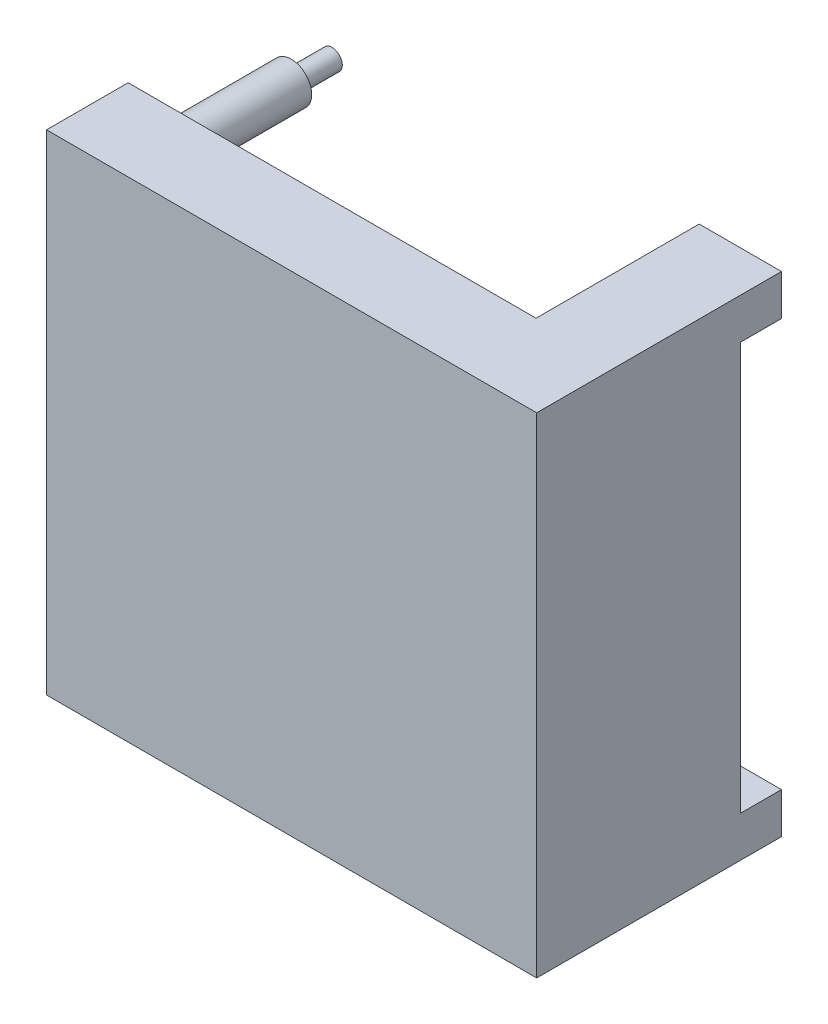
SolidWorks part; units mm, degrees
ref_plane "前视基准面" through (0, 0, 0) normal (0, 0, 1) x (1, 0, 0)
ref_plane "上视基准面" through (0, 0, 0) normal (0, 1, 0) x (1, 0, 0)
ref_plane "右视基准面" through (0, 0, 0) normal (1, 0, 0) x (0, 0, -1)
sketch "草图1" plane through (0, 0, 0) normal (0, 1, 0) x (1, 0, 0)
  line L0 (0, 0) -> (120.1627, 0)
  line L1 (120.1627, 0) -> (120.1627, 60)
  line L2 (120.1627, 60) -> (100, 60)
  line L3 (100, 60) -> (100, 20)
  line L4 (100, 20) -> (0, 20)
  line L5 (0, 20) -> (0, 0)
extrude "凸台-拉伸1" add sketch "草图1" along normal blind 60
sketch "草图3" plane through (120.1627, 0, 0) normal (1, 0, 0) x (0, 0, -1)
  line L0 (60, 50) -> (60, 10)
  line L1 (60, 60) -> (60, 0) construction
  line L2 (60, 10) -> (50, 10)
  line L3 (50, 10) -> (50, 50)
  line L5 (60, 50) -> (50, 50)
extrude "切除-拉伸2" cut sketch "草图3" against normal through all
sketch "草图4" plane through (0, 0, -20) normal (0, 0, -1) x (-1, 0, 0)
  line L2 (-100, 0) -> (0, 0) construction
  circle A0 centre (-10, 10) radius 5
  circle A1 centre (-10, 50) radius 5
  dimension "D1" = 10
sketch "草图6" plane through (0, 0, 0) normal (0, -1, 0) x (1, 0, 0)
  line L0 (42.3732, -30.9565) -> (41.9663, -30.9565)
sketch "草图7" plane through (0, 60, 0) normal (0, 1, 0) x (1, 0, 0)
  line L0 (0, 20) -> (0, 0)
  line L1 (0, 0) -> (120.1627, 0)
  line L2 (120.1627, 0) -> (120.1627, 60)
  line L3 (120.1627, 60) -> (100, 60)
  line L4 (100, 60) -> (100, 20)
  line L5 (100, 20) -> (0, 20)
extrude "凸台-拉伸4" add sketch "草图7" along normal blind 30
sketch "草图8" plane through (0, 0, 0) normal (0, -1, 0) x (1, 0, 0)
  line L0 (0, -20) -> (0, 0)
  line L1 (0, 0) -> (120.1627, 0)
  line L2 (120.1627, 0) -> (120.1627, -60)
  line L3 (120.1627, -60) -> (100, -60)
  line L4 (100, -60) -> (100, -20)
  line L5 (100, -20) -> (0, -20)
extrude "凸台-拉伸5" add sketch "草图8" along normal blind 30
sketch "草图9" plane through (0, 0, -20) normal (0, 0, -1) x (-1, 0, 0)
  line L0 (0, 30) -> (-20, 30)
  line L1 (0, 90) -> (0, -30) construction
  line L2 (-10, 30) -> (-10, -20)
  circle A0 centre (-10, -20) radius 5
  circle A1 centre (-10, 80) radius 5
extrude "凸台-拉伸6" add sketch "草图9" along normal blind 30 contours A1 | A0
sketch "草图10" plane through (0, 0, -50) normal (0, 0, -1) x (-1, 0, 0)
  circle A0 centre (-10, -20) radius 2.5
  circle A1 centre (-10, 80) radius 2.5
extrude "凸台-拉伸7" add sketch "草图10" along normal blind 10
sketch "草图11" plane through (0, 0, -60) normal (0, 0, -1) x (-1, 0, 0)
  line L0 (-120.1627, 10) -> (-100, 10)
  line L1 (-100, 10) -> (-100, -20)
  line L2 (-100, 90) -> (-100, -30) construction
  line L3 (-100, -20) -> (-120.1627, -20)
  line L4 (-120.1627, 10) -> (-120.1627, -30) construction
  line L5 (-120.1627, -20) -> (-120.1627, 10)
  line L6 (-120.1627, 50) -> (-100, 50)
  line L7 (-100, 50) -> (-100, 80)
  line L8 (-100, 90) -> (-100, 50) construction
  line L9 (-100, 80) -> (-120.1627, 80)
  line L10 (-120.1627, 90) -> (-120.1627, 50) construction
  line L11 (-120.1627, 80) -> (-120.1627, 50)
extrude "切除-拉伸3" cut sketch "草图11" against normal blind 10
sketch "草图12" plane through (0, 0, -60) normal (0, 0, -1) x (-1, 0, 0)
  circle A0 centre (-10, -20) radius 5
sketch "草图13" plane through (0, 0, -60) normal (0, 0, -1) x (-1, 0, 0)
  circle A0 centre (-10, 80) radius 5
